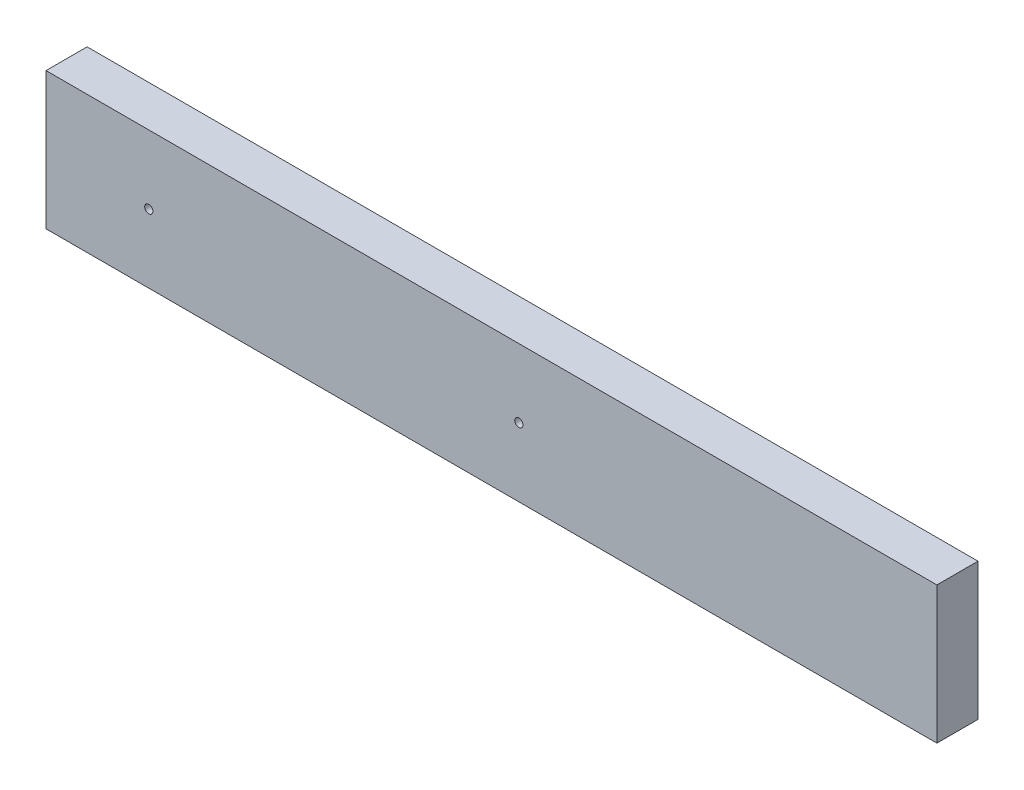
SolidWorks part; units mm, degrees
material "Pine"
ref_plane "Front Plane" through (0, 0, 0) normal (0, 0, 1) x (1, 0, 0)
ref_plane "Top Plane" through (0, 0, 0) normal (0, 1, 0) x (1, 0, 0)
ref_plane "Right Plane" through (0, 0, 0) normal (1, 0, 0) x (0, 0, -1)
sketch "Sketch1" plane through (0, 0, 0) normal (0, 0, 1) x (1, 0, 0)
  line L1 (-325, 50) -> (325, 50)
  line L2 (-325, 50) -> (-325, -50)
  line L3 (-325, -50) -> (325, -50)
  line L4 (325, 50) -> (325, -50)
  line L5 (-325, 50) -> (325, -50) construction
  line L6 (-325, -50) -> (325, 50) construction
  point P0 (0, 0)
  dimension "D1" = 100
  dimension "D2" = 650
extrude "Boss-Extrude1" add sketch "Sketch1" along normal blind 30
sketch "Sketch2" plane through (0, 0, 0) normal (0, 0, 1) x (1, 0, 0)
  circle A0 centre (20, 0) radius 3
  circle A1 centre (-250, 0) radius 3
  dimension "D1" = 6
  dimension "D2" = 20
  dimension "D3" = 250
extrude "Cut-Extrude1" cut sketch "Sketch2" along normal through all
